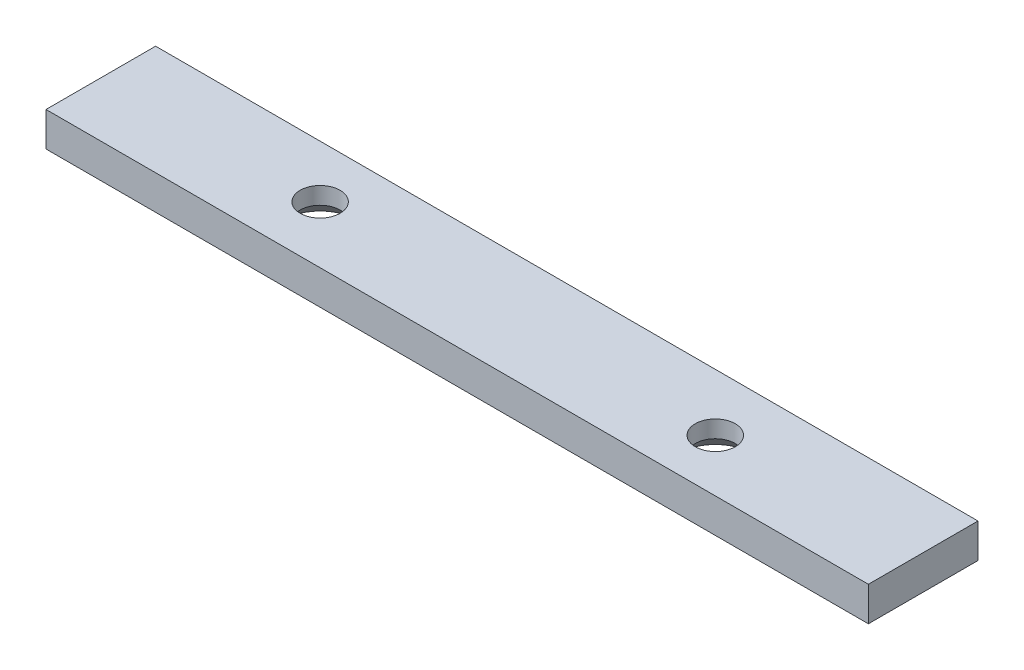
SolidWorks part; units mm, degrees
ref_plane "Front Plane" through (0, 0, 0) normal (0, 0, 1) x (1, 0, 0)
ref_plane "Top Plane" through (0, 0, 0) normal (0, 1, 0) x (1, 0, 0)
ref_plane "Right Plane" through (0, 0, 0) normal (1, 0, 0) x (0, 0, -1)
sketch "Sketch1" plane through (0, 0, 0) normal (0, 1, 0) x (1, 0, 0)
  line L0 (0, 0) -> (38, 0)
  line L1 (38, 0) -> (108, 0)
  line L2 (108, 0) -> (144, 0)
  line L3 (144, 0) -> (144, 19.1942)
  line L4 (144, 19.1942) -> (0, 19.1942)
  line L5 (0, 19.1942) -> (0, 0)
  circle A0 centre (38, 10) radius 3.5
  circle A1 centre (108, 9.1942) radius 3.5
  circle A2 centre (38, 10) radius 1.5
  circle A3 centre (108, 9.1942) radius 1.5
  dimension "D1" = 7
  dimension "D2" = 144
  dimension "D3" = 70
  dimension "D4" = 38
  dimension "D5" = 10
extrude "Boss-Extrude1" add sketch "Sketch1" along normal blind 6 contours L4 L5 L0 L1 L2 L3 A1 A0
chamfer "Chamfer1" distance 3 angle 45 2 edges at (38, 0, -6.5) (108, 0, -5.6942)
